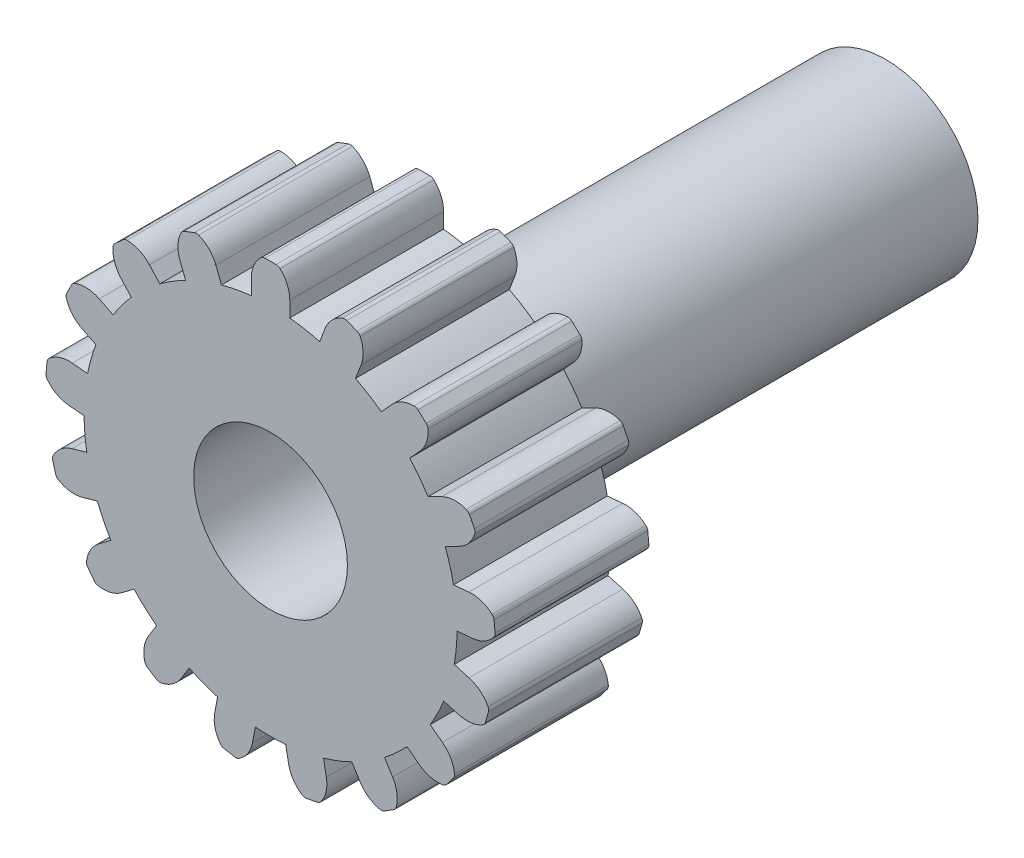
SolidWorks part; units mm, degrees
ref_plane "Front Plane" through (0, 0, 0) normal (0, 0, 1) x (1, 0, 0)
ref_plane "Top Plane" through (0, 0, 0) normal (0, 1, 0) x (1, 0, 0)
ref_plane "Right Plane" through (0, 0, 0) normal (1, 0, 0) x (0, 0, -1)
sketch "Sketch1" plane through (0, 0, 0) normal (0, 0, 1) x (1, 0, 0)
  circle A0 centre (0, 0) radius 24.2552
  dimension "D1" = 48.5104
extrude "Boss-Extrude1" add sketch "Sketch1" along normal mid plane 20
sketch "Sketch2" plane through (0, 0, 10) normal (0, 0, 1) x (1, 0, 0)
  line L0 (0, 24.2552) -> (0, 29.2552) construction
  line L1 (2.5, 24.126) -> (2.5, 26.126)
  line L2 (-2.5, 24.126) -> (-2.5, 26.126)
  line L3 (-2.5, 24.2552) -> (-2.5, 29.2552) construction
  line L4 (2.5, 24.2552) -> (2.5, 29.2552) construction
  line L5 (1, 24.2552) -> (1, 29.2552) construction
  line L6 (-1, 24.2552) -> (-1, 29.2552) construction
  line L7 (0, 24.2552) -> (0, 16.4357) construction
  line L8 (-0.7212, 29.2552) -> (0.7212, 29.2552)
  circle A0 centre (0, 0) radius 24.2552 construction
  arc A1 (2.5, 24.126) -> (-2.5, 24.126) centre (0, 0) ccw
  arc A2 (-2.5, 26.126) -> (-1.2338, 29.0527) centre (1.5, 26.1327) cw
  arc A3 (-1.2338, 29.0527) -> (-0.7212, 29.2552) centre (-0.7212, 28.5052) cw
  arc A4 (2.5, 26.126) -> (1.2338, 29.0527) centre (-1.5, 26.1327) ccw
  arc A5 (1.2338, 29.0527) -> (0.7212, 29.2552) centre (0.7212, 28.5052) ccw
  circle M1 centre (0, 0) radius 24.2552
  dimension "D5" = 0.75
  dimension "D1" = 4
  dimension "D2" = 2.5
  dimension "D3" = 2
  dimension "D4" = 1
  dimension "D6" = 5
extrude "Boss-Extrude2" add sketch "Sketch2" against normal through all contours L1 A4 L8 A2 L2 M1
pattern_circular "CirPattern1" count 17 over 360 about axis through (0, 0, 0) along (0, 0, 1) of "Boss-Extrude2"
sketch "Sketch3" plane through (0, 0, 10) normal (0, 0, 1) x (1, 0, 0)
  circle A0 centre (0, 0) radius 12
  dimension "D1" = 24
extrude "Cut-Extrude1" cut sketch "Sketch3" against normal blind 20
sketch "Sketch4" plane through (0, 0, 10) normal (0, 0, 1) x (1, 0, 0)
  circle A0 centre (0, 0) radius 12 construction
  circle A1 centre (0, 0) radius 12
  circle A2 centre (0, 0) radius 10
  dimension "D1" = 20
extrude "Boss-Extrude3" add sketch "Sketch4" against normal blind 80
sketch "Sketch5" plane through (0, 0, -70) normal (0, 0, -1) x (-1, 0, 0)
  line L0 (-10, 0) -> (0, 0) construction
  line L1 (-10, 0) -> (-10, -1) construction
  line L2 (-10.971, 0.7609) -> (-10.971, -1.2391)
  line L3 (-9.9229, -1.2391) -> (-10.971, -1.2391)
  line L9 (-9.971, 0.7609) -> (-10.971, 0.7609)
  circle A0 centre (0, 0) radius 10 construction
  arc A2 (-9.971, 0.7609) -> (-9.9229, -1.2391) centre (0, 0) ccw
  point P1 (-9.9229, -1.2391)
  dimension "D1" = 1
  dimension "D2" = 1
  dimension "D3" = 2
  dimension "D4" = 1
extrude "Cut-Extrude2" cut sketch "Sketch5" against normal blind 20
